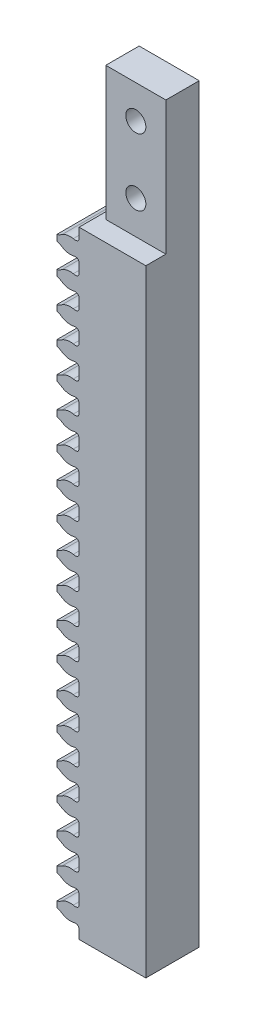
SolidWorks part; units mm, degrees
ref_plane "Front Plane" through (0, 0, 0) normal (0, 0, 1) x (1, 0, 0)
ref_plane "Top Plane" through (0, 0, 0) normal (0, 1, 0) x (1, 0, 0)
ref_plane "Right Plane" through (0, 0, 0) normal (1, 0, 0) x (0, 0, -1)
sketch "Sketch1" plane through (0, 0, 0) normal (0, 0, 1) x (1, 0, 0)
  line L1 (-6.8638, 24.1992) -> (-6.8638, 25.7119)
  line L2 (-10.205, 22.2603) -> (-10.205, 23.1007)
  line L4 (-6.8638, 19.6492) -> (-6.8638, 21.1619)
  line L5 (-10.205, 23.1007) -> (-10.205, 22.6805)
  line L6 (-6.8638, 28.7492) -> (-6.8638, 30.2619)
  line L7 (-10.205, 26.8103) -> (-10.205, 27.6507)
  line L8 (-10.205, 27.6507) -> (-10.205, 27.2305)
  line L9 (-6.8638, 33.2992) -> (-6.8638, 34.8119)
  line L10 (-10.205, 31.3603) -> (-10.205, 32.2007)
  line L11 (-10.205, 32.2007) -> (-10.205, 31.7805)
  line L12 (-6.8638, 37.8492) -> (-6.8638, 39.3619)
  line L13 (-10.205, 35.9103) -> (-10.205, 36.7507)
  line L14 (-10.205, 36.7507) -> (-10.205, 36.3305)
  line L15 (-6.8638, 42.3992) -> (-6.8638, 43.9119)
  line L16 (-10.205, 40.4603) -> (-10.205, 41.3007)
  line L17 (-10.205, 41.3007) -> (-10.205, 40.8805)
  line L18 (-6.8638, 46.9492) -> (-6.8638, 48.4619)
  line L19 (-10.205, 45.0103) -> (-10.205, 45.8507)
  line L20 (-10.205, 45.8507) -> (-10.205, 45.4305)
  line L21 (-6.8638, 51.4992) -> (-6.8638, 53.0119)
  line L22 (-10.205, 49.5603) -> (-10.205, 50.4007)
  line L23 (-10.205, 50.4007) -> (-10.205, 49.9805)
  line L24 (-6.8638, 56.0492) -> (-6.8638, 57.5619)
  line L25 (-10.205, 54.1103) -> (-10.205, 54.9507)
  line L26 (-10.205, 54.9507) -> (-10.205, 54.5305)
  line L27 (-6.8638, 60.5992) -> (-6.8638, 62.1119)
  line L28 (-10.205, 58.6603) -> (-10.205, 59.5007)
  line L29 (-10.205, 59.5007) -> (-10.205, 59.0805)
  line L30 (-6.8638, 65.1492) -> (-6.8638, 66.6619)
  line L31 (-10.205, 63.2103) -> (-10.205, 64.0507)
  line L32 (-10.205, 64.0507) -> (-10.205, 63.6305)
  line L33 (-6.8638, 69.6992) -> (-6.8638, 71.2119)
  line L34 (-10.205, 67.7603) -> (-10.205, 68.6007)
  line L35 (-10.205, 68.6007) -> (-10.205, 68.1805)
  line L36 (-6.8638, 74.2492) -> (-6.8638, 75.7619)
  line L37 (-10.205, 72.3103) -> (-10.205, 73.1507)
  line L38 (-10.205, 73.1507) -> (-10.205, 72.7305)
  line L39 (-6.8638, 78.7992) -> (-6.8638, 80.3119)
  line L40 (-10.205, 76.8603) -> (-10.205, 77.7007)
  line L41 (-10.205, 77.7007) -> (-10.205, 77.2805)
  line L42 (-6.8638, 83.3492) -> (-6.8638, 84.8619)
  line L43 (-10.205, 81.4103) -> (-10.205, 82.2507)
  line L44 (-10.205, 82.2507) -> (-10.205, 81.8305)
  line L45 (-6.8638, 87.8992) -> (-6.8638, 89.4119)
  line L46 (-10.205, 85.9603) -> (-10.205, 86.8007)
  line L47 (-10.205, 86.8007) -> (-10.205, 86.3805)
  line L48 (-6.8638, 92.4492) -> (-6.8638, 93.9619)
  line L49 (-10.205, 90.5103) -> (-10.205, 91.3507)
  line L50 (-10.205, 91.3507) -> (-10.205, 90.9305)
  line L51 (-6.8638, 96.9992) -> (-6.8638, 98.5119)
  line L52 (-10.205, 95.0603) -> (-10.205, 95.9007)
  line L53 (-10.205, 95.9007) -> (-10.205, 95.4805)
  line L54 (-6.8638, 101.5492) -> (-6.8638, 103.0619)
  line L55 (-10.205, 99.6103) -> (-10.205, 100.4507)
  line L56 (-10.205, 100.4507) -> (-10.205, 100.0305)
  line L57 (-6.8638, 106.0992) -> (-6.8638, 107.6119)
  line L58 (-10.205, 104.1603) -> (-10.205, 105.0007)
  line L59 (-10.205, 105.0007) -> (-10.205, 104.5805)
  line L60 (-6.8638, 107.6119) -> (3.1362, 107.6119)
  line L62 (-2.6436, 15.2239) -> (-6.8638, 15.2239)
  line L63 (-6.8638, 15.2239) -> (-6.8638, 16.6119)
  line L65 (-2.6436, 15.2239) -> (3.1362, 15.2239)
  line L68 (3.1362, 15.2239) -> (3.1362, 107.6119)
  line L72 (-10.205, 17.7103) -> (-10.205, 18.5507)
  line L73 (-10.205, 18.5507) -> (-10.205, 18.1305)
  arc A7 (-10.205, 23.1007) -> (-9.4013, 23.4885) centre (-10.9092, 25.5871) ccw
  arc A12 (-9.4013, 23.4885) -> (-7.7272, 23.7982) centre (-8.1678, 21.5007) cw
  arc A13 (-7.7272, 23.7982) -> (-7.0659, 23.8401) centre (-7.4477, 24.6272) ccw
  arc A14 (-7.7272, 21.5628) -> (-7.0659, 21.521) centre (-7.4477, 20.7338) cw
  arc A15 (-9.4013, 21.8725) -> (-7.7272, 21.5628) centre (-8.1678, 23.8603) ccw
  arc A16 (-10.205, 22.2603) -> (-9.4013, 21.8725) centre (-10.9092, 19.7739) cw
  arc A17 (-7.0659, 21.521) -> (-6.8638, 21.1619) centre (-7.5131, 21.0328) cw
  arc A18 (-7.0659, 23.8401) -> (-6.8638, 24.1992) centre (-7.5131, 24.3282) ccw
  arc A19 (-10.205, 27.6507) -> (-9.4013, 28.0385) centre (-10.9092, 30.1371) ccw
  arc A20 (-9.4013, 28.0385) -> (-7.7272, 28.3482) centre (-8.1678, 26.0507) cw
  arc A21 (-7.7272, 28.3482) -> (-7.0659, 28.3901) centre (-7.4477, 29.1772) ccw
  arc A22 (-7.7272, 26.1128) -> (-7.0659, 26.071) centre (-7.4477, 25.2838) cw
  arc A23 (-9.4013, 26.4225) -> (-7.7272, 26.1128) centre (-8.1678, 28.4103) ccw
  arc A24 (-10.205, 26.8103) -> (-9.4013, 26.4225) centre (-10.9092, 24.3239) cw
  arc A25 (-7.0659, 26.071) -> (-6.8638, 25.7119) centre (-7.5131, 25.5828) cw
  arc A26 (-7.0659, 28.3901) -> (-6.8638, 28.7492) centre (-7.5131, 28.8782) ccw
  arc A27 (-10.205, 32.2007) -> (-9.4013, 32.5885) centre (-10.9092, 34.6871) ccw
  arc A28 (-9.4013, 32.5885) -> (-7.7272, 32.8982) centre (-8.1678, 30.6007) cw
  arc A29 (-7.7272, 32.8982) -> (-7.0659, 32.9401) centre (-7.4477, 33.7272) ccw
  arc A30 (-7.7272, 30.6628) -> (-7.0659, 30.621) centre (-7.4477, 29.8338) cw
  arc A31 (-9.4013, 30.9725) -> (-7.7272, 30.6628) centre (-8.1678, 32.9603) ccw
  arc A32 (-10.205, 31.3603) -> (-9.4013, 30.9725) centre (-10.9092, 28.8739) cw
  arc A33 (-7.0659, 30.621) -> (-6.8638, 30.2619) centre (-7.5131, 30.1328) cw
  arc A34 (-7.0659, 32.9401) -> (-6.8638, 33.2992) centre (-7.5131, 33.4282) ccw
  arc A35 (-10.205, 36.7507) -> (-9.4013, 37.1385) centre (-10.9092, 39.2371) ccw
  arc A36 (-9.4013, 37.1385) -> (-7.7272, 37.4482) centre (-8.1678, 35.1507) cw
  arc A37 (-7.7272, 37.4482) -> (-7.0659, 37.4901) centre (-7.4477, 38.2772) ccw
  arc A38 (-7.7272, 35.2128) -> (-7.0659, 35.171) centre (-7.4477, 34.3838) cw
  arc A39 (-9.4013, 35.5225) -> (-7.7272, 35.2128) centre (-8.1678, 37.5103) ccw
  arc A40 (-10.205, 35.9103) -> (-9.4013, 35.5225) centre (-10.9092, 33.4239) cw
  arc A41 (-7.0659, 35.171) -> (-6.8638, 34.8119) centre (-7.5131, 34.6828) cw
  arc A42 (-7.0659, 37.4901) -> (-6.8638, 37.8492) centre (-7.5131, 37.9782) ccw
  arc A43 (-10.205, 41.3007) -> (-9.4013, 41.6885) centre (-10.9092, 43.7871) ccw
  arc A44 (-9.4013, 41.6885) -> (-7.7272, 41.9982) centre (-8.1678, 39.7007) cw
  arc A45 (-7.7272, 41.9982) -> (-7.0659, 42.0401) centre (-7.4477, 42.8272) ccw
  arc A46 (-7.7272, 39.7628) -> (-7.0659, 39.721) centre (-7.4477, 38.9338) cw
  arc A47 (-9.4013, 40.0725) -> (-7.7272, 39.7628) centre (-8.1678, 42.0603) ccw
  arc A48 (-10.205, 40.4603) -> (-9.4013, 40.0725) centre (-10.9092, 37.9739) cw
  arc A49 (-7.0659, 39.721) -> (-6.8638, 39.3619) centre (-7.5131, 39.2328) cw
  arc A50 (-7.0659, 42.0401) -> (-6.8638, 42.3992) centre (-7.5131, 42.5282) ccw
  arc A51 (-10.205, 45.8507) -> (-9.4013, 46.2385) centre (-10.9092, 48.3371) ccw
  arc A52 (-9.4013, 46.2385) -> (-7.7272, 46.5482) centre (-8.1678, 44.2507) cw
  arc A53 (-7.7272, 46.5482) -> (-7.0659, 46.5901) centre (-7.4477, 47.3772) ccw
  arc A54 (-7.7272, 44.3128) -> (-7.0659, 44.271) centre (-7.4477, 43.4838) cw
  arc A55 (-9.4013, 44.6225) -> (-7.7272, 44.3128) centre (-8.1678, 46.6103) ccw
  arc A56 (-10.205, 45.0103) -> (-9.4013, 44.6225) centre (-10.9092, 42.5239) cw
  arc A57 (-7.0659, 44.271) -> (-6.8638, 43.9119) centre (-7.5131, 43.7828) cw
  arc A58 (-7.0659, 46.5901) -> (-6.8638, 46.9492) centre (-7.5131, 47.0782) ccw
  arc A59 (-10.205, 50.4007) -> (-9.4013, 50.7885) centre (-10.9092, 52.8871) ccw
  arc A60 (-9.4013, 50.7885) -> (-7.7272, 51.0982) centre (-8.1678, 48.8007) cw
  arc A61 (-7.7272, 51.0982) -> (-7.0659, 51.1401) centre (-7.4477, 51.9272) ccw
  arc A62 (-7.7272, 48.8628) -> (-7.0659, 48.821) centre (-7.4477, 48.0338) cw
  arc A63 (-9.4013, 49.1725) -> (-7.7272, 48.8628) centre (-8.1678, 51.1603) ccw
  arc A64 (-10.205, 49.5603) -> (-9.4013, 49.1725) centre (-10.9092, 47.0739) cw
  arc A65 (-7.0659, 48.821) -> (-6.8638, 48.4619) centre (-7.5131, 48.3328) cw
  arc A66 (-7.0659, 51.1401) -> (-6.8638, 51.4992) centre (-7.5131, 51.6282) ccw
  arc A67 (-10.205, 54.9507) -> (-9.4013, 55.3385) centre (-10.9092, 57.4371) ccw
  arc A68 (-9.4013, 55.3385) -> (-7.7272, 55.6482) centre (-8.1678, 53.3507) cw
  arc A69 (-7.7272, 55.6482) -> (-7.0659, 55.6901) centre (-7.4477, 56.4772) ccw
  arc A70 (-7.7272, 53.4128) -> (-7.0659, 53.371) centre (-7.4477, 52.5838) cw
  arc A71 (-9.4013, 53.7225) -> (-7.7272, 53.4128) centre (-8.1678, 55.7103) ccw
  arc A72 (-10.205, 54.1103) -> (-9.4013, 53.7225) centre (-10.9092, 51.6239) cw
  arc A73 (-7.0659, 53.371) -> (-6.8638, 53.0119) centre (-7.5131, 52.8828) cw
  arc A74 (-7.0659, 55.6901) -> (-6.8638, 56.0492) centre (-7.5131, 56.1782) ccw
  arc A75 (-10.205, 59.5007) -> (-9.4013, 59.8885) centre (-10.9092, 61.9871) ccw
  arc A76 (-9.4013, 59.8885) -> (-7.7272, 60.1982) centre (-8.1678, 57.9007) cw
  arc A77 (-7.7272, 60.1982) -> (-7.0659, 60.2401) centre (-7.4477, 61.0272) ccw
  arc A78 (-7.7272, 57.9628) -> (-7.0659, 57.921) centre (-7.4477, 57.1338) cw
  arc A79 (-9.4013, 58.2725) -> (-7.7272, 57.9628) centre (-8.1678, 60.2603) ccw
  arc A80 (-10.205, 58.6603) -> (-9.4013, 58.2725) centre (-10.9092, 56.1739) cw
  arc A81 (-7.0659, 57.921) -> (-6.8638, 57.5619) centre (-7.5131, 57.4328) cw
  arc A82 (-7.0659, 60.2401) -> (-6.8638, 60.5992) centre (-7.5131, 60.7282) ccw
  arc A83 (-10.205, 64.0507) -> (-9.4013, 64.4385) centre (-10.9092, 66.5371) ccw
  arc A84 (-9.4013, 64.4385) -> (-7.7272, 64.7482) centre (-8.1678, 62.4507) cw
  arc A85 (-7.7272, 64.7482) -> (-7.0659, 64.7901) centre (-7.4477, 65.5772) ccw
  arc A86 (-7.7272, 62.5128) -> (-7.0659, 62.471) centre (-7.4477, 61.6838) cw
  arc A87 (-9.4013, 62.8225) -> (-7.7272, 62.5128) centre (-8.1678, 64.8103) ccw
  arc A88 (-10.205, 63.2103) -> (-9.4013, 62.8225) centre (-10.9092, 60.7239) cw
  arc A89 (-7.0659, 62.471) -> (-6.8638, 62.1119) centre (-7.5131, 61.9828) cw
  arc A90 (-7.0659, 64.7901) -> (-6.8638, 65.1492) centre (-7.5131, 65.2782) ccw
  arc A91 (-10.205, 68.6007) -> (-9.4013, 68.9885) centre (-10.9092, 71.0871) ccw
  arc A92 (-9.4013, 68.9885) -> (-7.7272, 69.2982) centre (-8.1678, 67.0007) cw
  arc A93 (-7.7272, 69.2982) -> (-7.0659, 69.3401) centre (-7.4477, 70.1272) ccw
  arc A94 (-7.7272, 67.0628) -> (-7.0659, 67.021) centre (-7.4477, 66.2338) cw
  arc A95 (-9.4013, 67.3725) -> (-7.7272, 67.0628) centre (-8.1678, 69.3603) ccw
  arc A96 (-10.205, 67.7603) -> (-9.4013, 67.3725) centre (-10.9092, 65.2739) cw
  arc A97 (-7.0659, 67.021) -> (-6.8638, 66.6619) centre (-7.5131, 66.5328) cw
  arc A98 (-7.0659, 69.3401) -> (-6.8638, 69.6992) centre (-7.5131, 69.8282) ccw
  arc A99 (-10.205, 73.1507) -> (-9.4013, 73.5385) centre (-10.9092, 75.6371) ccw
  arc A100 (-9.4013, 73.5385) -> (-7.7272, 73.8482) centre (-8.1678, 71.5507) cw
  arc A101 (-7.7272, 73.8482) -> (-7.0659, 73.8901) centre (-7.4477, 74.6772) ccw
  arc A102 (-7.7272, 71.6128) -> (-7.0659, 71.571) centre (-7.4477, 70.7838) cw
  arc A103 (-9.4013, 71.9225) -> (-7.7272, 71.6128) centre (-8.1678, 73.9103) ccw
  arc A104 (-10.205, 72.3103) -> (-9.4013, 71.9225) centre (-10.9092, 69.8239) cw
  arc A105 (-7.0659, 71.571) -> (-6.8638, 71.2119) centre (-7.5131, 71.0828) cw
  arc A106 (-7.0659, 73.8901) -> (-6.8638, 74.2492) centre (-7.5131, 74.3782) ccw
  arc A107 (-10.205, 77.7007) -> (-9.4013, 78.0885) centre (-10.9092, 80.1871) ccw
  arc A108 (-9.4013, 78.0885) -> (-7.7272, 78.3982) centre (-8.1678, 76.1007) cw
  arc A109 (-7.7272, 78.3982) -> (-7.0659, 78.4401) centre (-7.4477, 79.2272) ccw
  arc A110 (-7.7272, 76.1628) -> (-7.0659, 76.121) centre (-7.4477, 75.3338) cw
  arc A111 (-9.4013, 76.4725) -> (-7.7272, 76.1628) centre (-8.1678, 78.4603) ccw
  arc A112 (-10.205, 76.8603) -> (-9.4013, 76.4725) centre (-10.9092, 74.3739) cw
  arc A113 (-7.0659, 76.121) -> (-6.8638, 75.7619) centre (-7.5131, 75.6328) cw
  arc A114 (-7.0659, 78.4401) -> (-6.8638, 78.7992) centre (-7.5131, 78.9282) ccw
  arc A115 (-10.205, 82.2507) -> (-9.4013, 82.6385) centre (-10.9092, 84.7371) ccw
  arc A116 (-9.4013, 82.6385) -> (-7.7272, 82.9482) centre (-8.1678, 80.6507) cw
  arc A117 (-7.7272, 82.9482) -> (-7.0659, 82.9901) centre (-7.4477, 83.7772) ccw
  arc A118 (-7.7272, 80.7128) -> (-7.0659, 80.671) centre (-7.4477, 79.8838) cw
  arc A119 (-9.4013, 81.0225) -> (-7.7272, 80.7128) centre (-8.1678, 83.0103) ccw
  arc A120 (-10.205, 81.4103) -> (-9.4013, 81.0225) centre (-10.9092, 78.9239) cw
  arc A121 (-7.0659, 80.671) -> (-6.8638, 80.3119) centre (-7.5131, 80.1828) cw
  arc A122 (-7.0659, 82.9901) -> (-6.8638, 83.3492) centre (-7.5131, 83.4782) ccw
  arc A123 (-10.205, 86.8007) -> (-9.4013, 87.1885) centre (-10.9092, 89.2871) ccw
  arc A124 (-9.4013, 87.1885) -> (-7.7272, 87.4982) centre (-8.1678, 85.2007) cw
  arc A125 (-7.7272, 87.4982) -> (-7.0659, 87.5401) centre (-7.4477, 88.3272) ccw
  arc A126 (-7.7272, 85.2628) -> (-7.0659, 85.221) centre (-7.4477, 84.4338) cw
  arc A127 (-9.4013, 85.5725) -> (-7.7272, 85.2628) centre (-8.1678, 87.5603) ccw
  arc A128 (-10.205, 85.9603) -> (-9.4013, 85.5725) centre (-10.9092, 83.4739) cw
  arc A129 (-7.0659, 85.221) -> (-6.8638, 84.8619) centre (-7.5131, 84.7328) cw
  arc A130 (-7.0659, 87.5401) -> (-6.8638, 87.8992) centre (-7.5131, 88.0282) ccw
  arc A131 (-10.205, 91.3507) -> (-9.4013, 91.7385) centre (-10.9092, 93.8371) ccw
  arc A132 (-9.4013, 91.7385) -> (-7.7272, 92.0482) centre (-8.1678, 89.7507) cw
  arc A133 (-7.7272, 92.0482) -> (-7.0659, 92.0901) centre (-7.4477, 92.8772) ccw
  arc A134 (-7.7272, 89.8128) -> (-7.0659, 89.771) centre (-7.4477, 88.9838) cw
  arc A135 (-9.4013, 90.1225) -> (-7.7272, 89.8128) centre (-8.1678, 92.1103) ccw
  arc A136 (-10.205, 90.5103) -> (-9.4013, 90.1225) centre (-10.9092, 88.0239) cw
  arc A137 (-7.0659, 89.771) -> (-6.8638, 89.4119) centre (-7.5131, 89.2828) cw
  arc A138 (-7.0659, 92.0901) -> (-6.8638, 92.4492) centre (-7.5131, 92.5782) ccw
  arc A139 (-10.205, 95.9007) -> (-9.4013, 96.2885) centre (-10.9092, 98.3871) ccw
  arc A140 (-9.4013, 96.2885) -> (-7.7272, 96.5982) centre (-8.1678, 94.3007) cw
  arc A141 (-7.7272, 96.5982) -> (-7.0659, 96.6401) centre (-7.4477, 97.4272) ccw
  arc A142 (-7.7272, 94.3628) -> (-7.0659, 94.321) centre (-7.4477, 93.5338) cw
  arc A143 (-9.4013, 94.6725) -> (-7.7272, 94.3628) centre (-8.1678, 96.6603) ccw
  arc A144 (-10.205, 95.0603) -> (-9.4013, 94.6725) centre (-10.9092, 92.5739) cw
  arc A145 (-7.0659, 94.321) -> (-6.8638, 93.9619) centre (-7.5131, 93.8328) cw
  arc A146 (-7.0659, 96.6401) -> (-6.8638, 96.9992) centre (-7.5131, 97.1282) ccw
  arc A147 (-10.205, 100.4507) -> (-9.4013, 100.8385) centre (-10.9092, 102.9371) ccw
  arc A148 (-9.4013, 100.8385) -> (-7.7272, 101.1482) centre (-8.1678, 98.8507) cw
  arc A149 (-7.7272, 101.1482) -> (-7.0659, 101.1901) centre (-7.4477, 101.9772) ccw
  arc A150 (-7.7272, 98.9128) -> (-7.0659, 98.871) centre (-7.4477, 98.0838) cw
  arc A151 (-9.4013, 99.2225) -> (-7.7272, 98.9128) centre (-8.1678, 101.2103) ccw
  arc A152 (-10.205, 99.6103) -> (-9.4013, 99.2225) centre (-10.9092, 97.1239) cw
  arc A153 (-7.0659, 98.871) -> (-6.8638, 98.5119) centre (-7.5131, 98.3828) cw
  arc A154 (-7.0659, 101.1901) -> (-6.8638, 101.5492) centre (-7.5131, 101.6782) ccw
  arc A155 (-10.205, 105.0007) -> (-9.4013, 105.3885) centre (-10.9092, 107.4871) ccw
  arc A156 (-9.4013, 105.3885) -> (-7.7272, 105.6982) centre (-8.1678, 103.4007) cw
  arc A157 (-7.7272, 105.6982) -> (-7.0659, 105.7401) centre (-7.4477, 106.5272) ccw
  arc A158 (-7.7272, 103.4628) -> (-7.0659, 103.421) centre (-7.4477, 102.6338) cw
  arc A159 (-9.4013, 103.7725) -> (-7.7272, 103.4628) centre (-8.1678, 105.7603) ccw
  arc A160 (-10.205, 104.1603) -> (-9.4013, 103.7725) centre (-10.9092, 101.6739) cw
  arc A161 (-7.0659, 103.421) -> (-6.8638, 103.0619) centre (-7.5131, 102.9328) cw
  arc A162 (-7.0659, 105.7401) -> (-6.8638, 106.0992) centre (-7.5131, 106.2282) ccw
  arc A293 (-10.205, 18.5507) -> (-9.4013, 18.9385) centre (-10.9092, 21.0371) ccw
  arc A294 (-9.4013, 18.9385) -> (-7.7272, 19.2482) centre (-8.1678, 16.9507) cw
  arc A295 (-7.7272, 19.2482) -> (-7.0659, 19.2901) centre (-7.4477, 20.0772) ccw
  arc A296 (-7.7272, 17.0128) -> (-7.0659, 16.971) centre (-7.4477, 16.1838) cw
  arc A297 (-9.4013, 17.3225) -> (-7.7272, 17.0128) centre (-8.1678, 19.3103) ccw
  arc A298 (-10.205, 17.7103) -> (-9.4013, 17.3225) centre (-10.9092, 15.2239) cw
  arc A299 (-7.0659, 16.971) -> (-6.8638, 16.6119) centre (-7.5131, 16.4828) cw
  arc A300 (-7.0659, 19.2901) -> (-6.8638, 19.6492) centre (-7.5131, 19.7782) ccw
  dimension "D1" = 20
  dimension "D3" = 10
extrude "Boss-Extrude1" add sketch "Sketch1" along normal blind 8
sketch "Sketch3" plane through (0, 0, 0) normal (0, 0, -1) x (-1, 0, 0)
  line L1 (-3.1362, 107.6119) -> (5.8638, 107.6119)
  line L2 (-3.1362, 107.6119) -> (-3.1362, 127.6119)
  line L3 (-3.1362, 127.6119) -> (5.8638, 127.6119)
  line L4 (5.8638, 107.6119) -> (5.8638, 127.6119)
  dimension "D1" = 9
  dimension "D2" = 20
extrude "Boss-Extrude2" add sketch "Sketch3" against normal blind 5
sketch "Sketch4" plane through (0, 0, 5) normal (0, 0, 1) x (1, 0, 0)
  line L1 (-5.8638, 127.6119) -> (3.1362, 127.6119)
  line L2 (-5.8638, 127.6119) -> (-5.8638, 107.6119)
  line L3 (-5.8638, 107.6119) -> (3.1362, 107.6119)
  line L4 (3.1362, 127.6119) -> (3.1362, 107.6119)
  line L5 (1.8405, 112.6119) -> (0.2384, 115.3869)
  line L6 (0.2384, 115.3869) -> (-2.9659, 115.3869)
  line L7 (-2.9659, 115.3869) -> (-4.5681, 112.6119)
  line L8 (-4.5681, 112.6119) -> (-2.9659, 109.8369)
  line L9 (-2.9659, 109.8369) -> (0.2384, 109.8369)
  line L10 (0.2384, 109.8369) -> (1.8405, 112.6119)
  line L11 (1.8405, 122.6119) -> (0.2384, 125.3869)
  line L12 (0.2384, 125.3869) -> (-2.9659, 125.3869)
  line L13 (-2.9659, 125.3869) -> (-4.5681, 122.6119)
  line L14 (-4.5681, 122.6119) -> (-2.9659, 119.8369)
  line L15 (-2.9659, 119.8369) -> (0.2384, 119.8369)
  line L16 (0.2384, 119.8369) -> (1.8405, 122.6119)
  circle A0 centre (-1.3638, 112.6119) radius 2.775 construction
  circle A1 centre (-1.3638, 122.6119) radius 2.775 construction
  circle A2 centre (-1.3638, 122.6119) radius 1.5
  circle A3 centre (-1.3638, 112.6119) radius 1.5
  point P6 (0, 0)
  dimension "D3" = 3
  dimension "D4" = 3
  dimension "D1" = 5.55
  dimension "D2" = 5.55
extrude "Cut-Extrude2" cut sketch "Sketch4" against normal blind 5 contours A3 | A2
